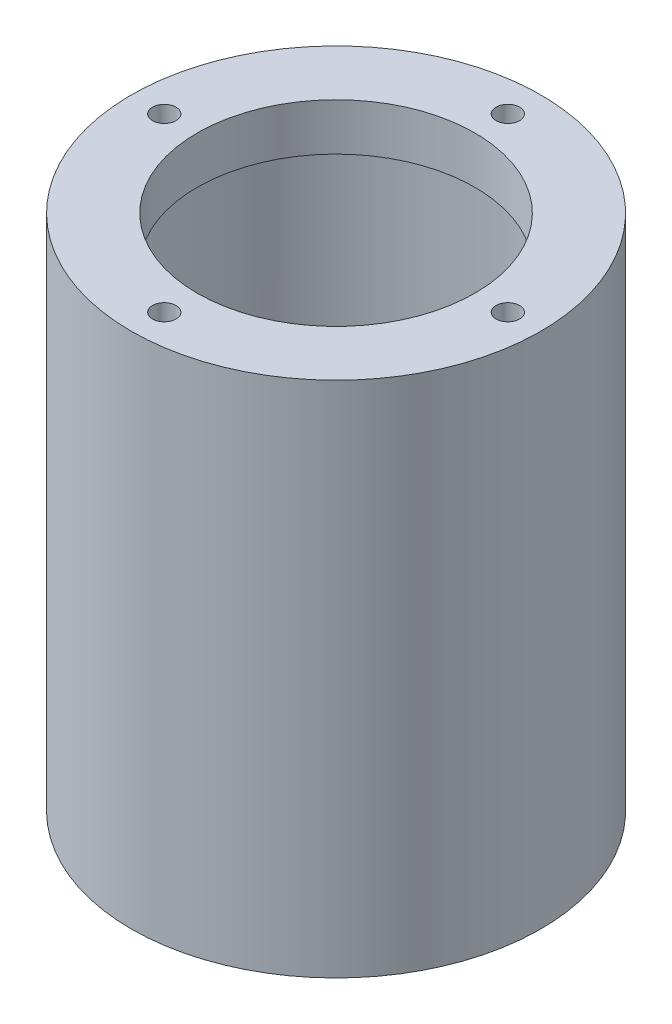
SolidWorks part; units mm, degrees
ref_plane "正面" through (0, 0, 0) normal (0, 0, 1) x (1, 0, 0)
ref_plane "平面" through (0, 0, 0) normal (0, 1, 0) x (1, 0, 0)
ref_plane "右側面" through (0, 0, 0) normal (1, 0, 0) x (0, 0, -1)
sketch "ｽｹｯﾁ1" plane through (0, 0, 0) normal (0, 1, 0) x (1, 0, 0)
  circle A0 centre (0, 0) radius 21.75
  circle A1 centre (0, 0) radius 14.75
  dimension "D1" = 29.5
  dimension "D2" = 43.5
extrude "ﾎﾞｽ - 押し出し1" add sketch "ｽｹｯﾁ1" along normal blind 55
sketch "ｽｹｯﾁ2" plane through (0, 55, 0) normal (0, 1, 0) x (1, 0, 0)
  circle A0 centre (0, 0) radius 14.75
  circle A1 centre (0, 0) radius 18.75
  circle A2 centre (0, 0) radius 14.75 construction
  circle A3 centre (0, 0) radius 21.75 construction
  dimension "D1" = 3
extrude "ｶｯﾄ - 押し出し1" cut sketch "ｽｹｯﾁ2" against normal through all from offset 5 offset against normal yes
sketch "ｽｹｯﾁ3" plane through (0, 55, 0) normal (0, 1, 0) x (1, 0, 0)
  line L0 (0, 0) -> (0, 14.75) construction
  line L1 (0, 14.75) -> (0, 18.25) construction
  line L2 (0, 18.25) -> (0, 21.75) construction
  circle A0 centre (0, 0) radius 18.25 construction
  circle A1 centre (0, 18.25) radius 1.25
  circle A2 centre (0, 0) radius 14.75 construction
  circle A3 centre (0, 0) radius 21.75 construction
  circle A4 centre (18.25, 0) radius 1.25
  circle A5 centre (0, -18.25) radius 1.25
  circle A6 centre (-18.25, 0) radius 1.25
  point P22 (0, 0)
  dimension "D1" = 2.5
  dimension "D2" = 4
extrude "ｶｯﾄ - 押し出し2" cut sketch "ｽｹｯﾁ3" against normal blind 5
